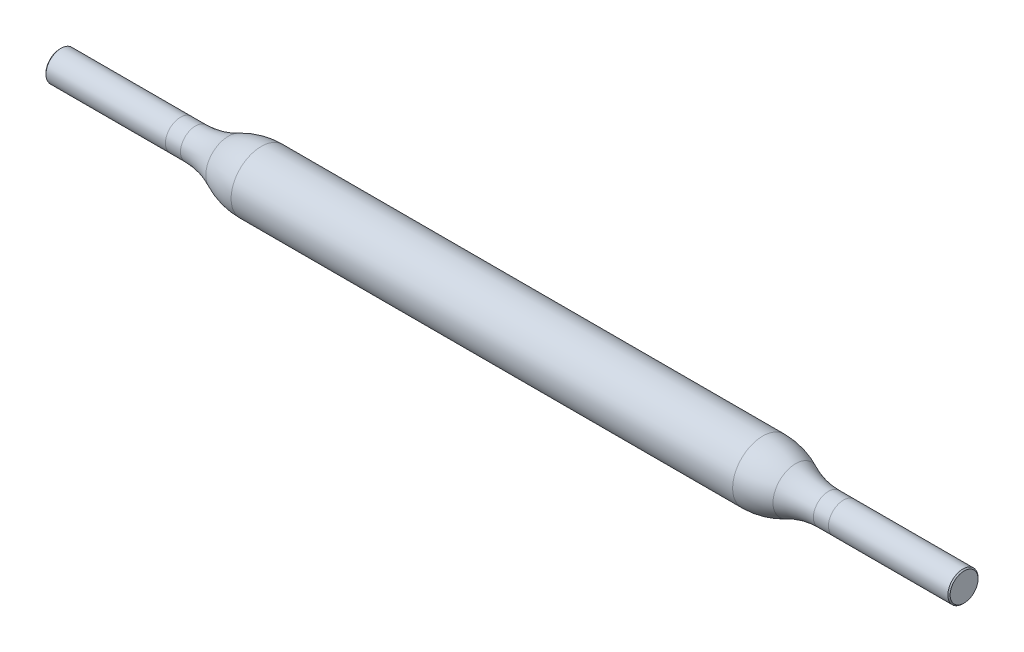
SolidWorks part; units mm, degrees
ref_plane "Front Plane" through (0, 0, 0) normal (0, 0, 1) x (1, 0, 0)
ref_plane "Top Plane" through (0, 0, 0) normal (0, 1, 0) x (1, 0, 0)
ref_plane "Right Plane" through (0, 0, 0) normal (1, 0, 0) x (0, 0, -1)
sketch "Sketch1" plane through (0, 0, 0) normal (0, 0, 1) x (1, 0, 0)
  line L0 (-30, 0) -> (30, 0)
  line L2 (-30, 0) -> (-30, 1)
  line L3 (-30, 1) -> (-21, 1)
  line L4 (-16.6411, 2) -> (16.6411, 2)
  line L9 (30, 1) -> (21, 1)
  line L10 (30, 0) -> (30, 1)
  arc A0 (-21, 1) -> (-18.8206, 1.5) centre (-21, 6) ccw
  arc A2 (21, 1) -> (18.8206, 1.5) centre (21, 6) cw
  arc A3 (18.8206, 1.5) -> (16.6411, 2) centre (16.6411, -3) ccw
  arc A4 (-16.6411, 2) -> (-18.8206, 1.5) centre (-16.6411, -3) ccw
  point P3 (0, 2)
  point P11 (0, 0)
  point P18 (-18, 2)
  point P19 (0, 0)
  dimension "D3" = 3
  dimension "D6" = 5
  dimension "D1" = 60
  dimension "D2" = 1
  dimension "D4" = 9
  dimension "D5" = 2
  dimension "D7" = 9
revolve "Revolve2" add sketch "Sketch1" angle 360 about L0
sketch "Sketch3" plane through (0, 0, 0) normal (0, 0, 1) x (1, 0, 0)
  line L0 (-22, 4.3502) -> (-22, -5.0352)
  line L1 (22, 4.3502) -> (22, -5.0352)
  line L2 (-30, 1) -> (-30, -1) construction
  line L3 (30, -1) -> (30, 1) construction
  dimension "D1" = 8
  dimension "D2" = 8
split line "Split Line1"
chamfer "Chamfer1" distance 0.075 angle 45 2 edges at (-30, 0, 1) (30, 0, 1)
